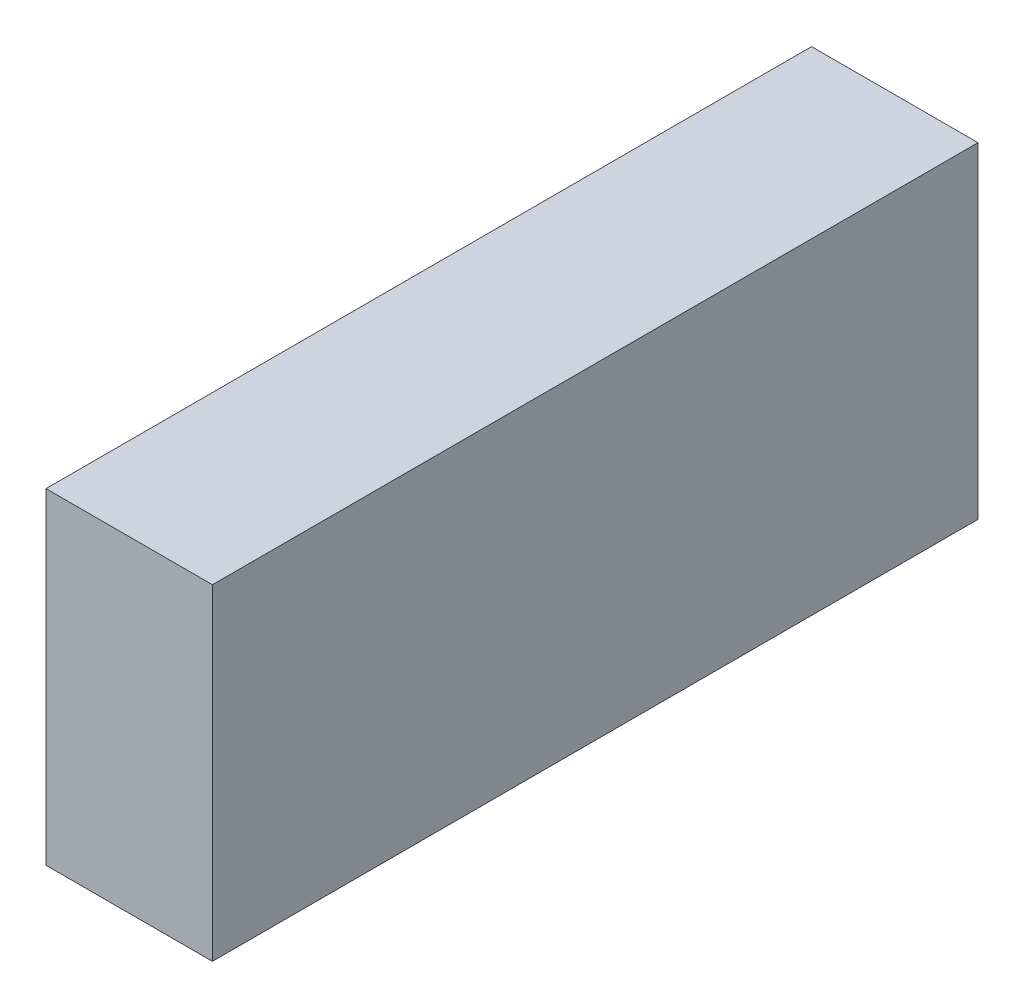
SolidWorks part; units mm, degrees
material "Porcelana cerâmica"
ref_plane "Plano frontal" through (0, 0, 0) normal (0, 0, 1) x (1, 0, 0)
ref_plane "Plano superior" through (0, 0, 0) normal (0, 1, 0) x (1, 0, 0)
ref_plane "Plano direito" through (0, 0, 0) normal (1, 0, 0) x (0, 0, -1)
sketch "Esboço1" plane through (0, 0, 0) normal (0, 0, 1) x (1, 0, 0)
  line L1 (0, 0) -> (50, 0)
  line L2 (0, 0) -> (0, 98)
  line L3 (0, 98) -> (50, 98)
  line L4 (50, 0) -> (50, 98)
  dimension "D1" = 98
  dimension "D2" = 50
extrude "Ressalto-extrusão1" add sketch "Esboço1" along normal blind 230
